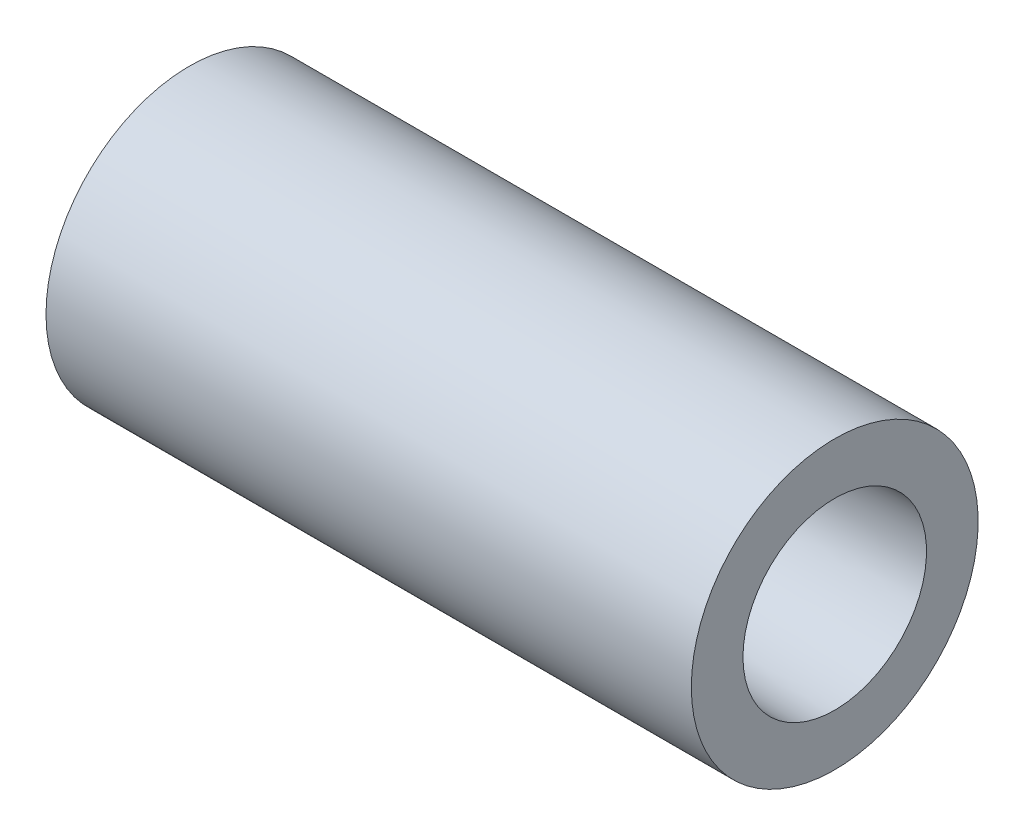
SolidWorks part; units mm, degrees
material "201 Tavlı Paslanmaz Çelik (SS)"
ref_plane "Ön Düzlem" through (0, 0, 0) normal (0, 0, 1) x (1, 0, 0)
ref_plane "Üst Düzlem" through (0, 0, 0) normal (0, 1, 0) x (1, 0, 0)
ref_plane "Sağ Düzlem" through (0, 0, 0) normal (1, 0, 0) x (0, 0, -1)
sketch "Çizim1" plane through (0, 0, 0) normal (0, 0, 1) x (1, 0, 0)
  line L7 (0, 10) -> (0, 6)
  line L9 (0, 10) -> (45, 10)
  line L10 (45, 10) -> (45, 6.4)
  line L11 (0, 0) -> (45, 0) construction
  spline S0 degree 2 poles (45, 6.4) (42.8663, 6.3585) (40.7362, 6.2424) (38.7621, 6.1347) (36.4803, 5.9413) (34.1571, 5.7444) (32.2339, 5.5267) (31.1669, 5.4059) (30.1159, 5.2704) (29.0581, 5.134) (28, 5) knots 0 0 0 0.25 0.25 0.5 0.5 0.75 0.75 0.875 0.875 1 1 1
  spline S1 degree 2 poles (28, 5) (27.4534, 4.9308) (26.6253, 4.8281) (25.3236, 4.6668) (25.25, 4.6576) (24.3249, 4.5424) (23.8737, 4.4838) (23.185, 4.3944) (22.4964, 4.3054) (20.837, 4.0908) (19.7487, 3.9724) (19.1269, 3.9048) (19.0644, 3.8978) (18.6743, 3.8543) (18.3793, 3.8169) (17.6086, 3.719) (17, 3.6) knots 0 0 0 0.125 0.125 0.25 0.25 0.375 0.375 0.5 0.5 0.75 0.75 0.8125 0.8125 0.875 0.875 1 1 1
  spline S2 degree 2 poles (17, 3.6) (16.9491, 3.59) (16.6169, 3.5224) (16.3833, 3.4748) (16.2336, 3.4484) (15.7938, 3.3708) (15.4727, 3.3663) (15.2754, 3.3635) (15.0983, 3.3856) (14.9252, 3.4072) (14.7297, 3.4606) (14.584, 3.5004) (14.3648, 3.5755) (14.0257, 3.6916) (14, 3.7) knots 0 0 0 0.125 0.125 0.25 0.25 0.5 0.5 0.625 0.625 0.75 0.75 0.875 0.875 1 1 1
  spline S3 degree 2 poles (14, 3.7) (13.7251, 3.7896) (13.38, 3.8762) (13.1626, 3.9308) (12.7551, 4.0224) (12.3267, 4.1188) (12.1309, 4.1671) (11.8406, 4.2386) (11.5124, 4.3348) (11.2729, 4.405) (10.8984, 4.5225) (10.3904, 4.6819) (10.2849, 4.7143) (9.6781, 4.9004) (9.0469, 5.0577) (8.4834, 5.1981) (7.7952, 5.3438) (7.2679, 5.4554) (6.5367, 5.5969) (5.6221, 5.7739) (5.2725, 5.8348) (4.5416, 5.9621) (4, 6) knots 0 0 0 0.0625 0.0625 0.125 0.125 0.1875 0.1875 0.25 0.25 0.3125 0.3125 0.375 0.375 0.5 0.5 0.625 0.625 0.75 0.75 0.875 0.875 1 1 1
  spline S4 degree 2 poles (4, 6) (3.5732, 6.0299) (3.0015, 6.0232) (2.7507, 6.0203) (2.5008, 6.0131) (2.2504, 6.0058) (2, 6) (0.9985, 5.9768) (0, 6) knots 0 0 0 0.25 0.25 0.375 0.375 0.5 0.5 1 1 1
  point P3 (0, 0)
  dimension "D1" = 4
revolve "Döndür1" add sketch "Çizim1" angle 360 about L11
